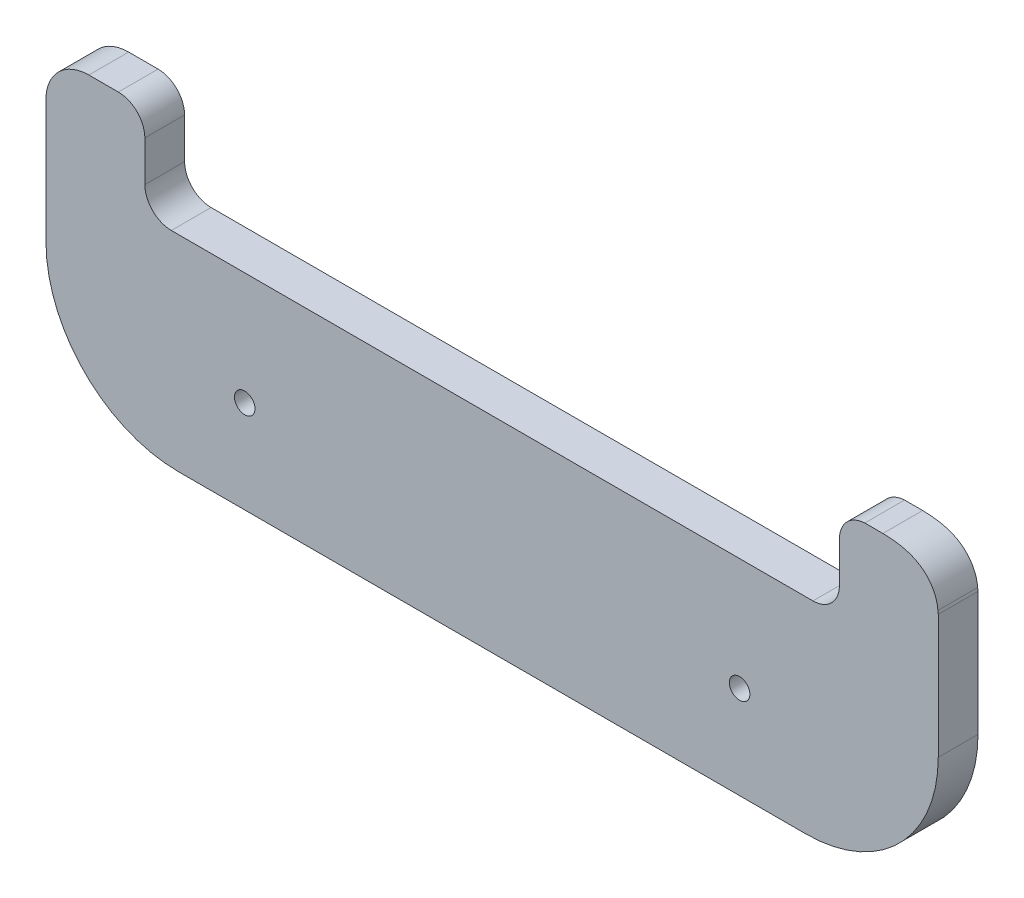
SolidWorks part; units mm, degrees
ref_plane "Płaszczyzna przednia" through (0, 0, 0) normal (0, 0, 1) x (1, 0, 0)
ref_plane "Płaszczyzna górna" through (0, 0, 0) normal (0, 1, 0) x (1, 0, 0)
ref_plane "Płaszczyzna prawa" through (0, 0, 0) normal (1, 0, 0) x (0, 0, -1)
sketch "Szkic1" plane through (0, 0, 0) normal (0, 0, 1) x (1, 0, 0)
  line L0 (559.3031, -401.1962) -> (679.1692, -401.1962)
  line L1 (552.8295, -407.6962) -> (552.8295, -426.2962) construction
  line L3 (667.5241, -446.2962) -> (572.8295, -446.2962) construction
  line L4 (687.5241, -419.2962) -> (687.5241, -426.2962) construction
  line L5 (552.8295, -407.6962) -> (552.8295, -426.2962)
  line L6 (667.5241, -446.2962) -> (572.8295, -446.2962)
  line L7 (687.4745, -407.1052) -> (687.5241, -407.5881)
  line L8 (687.5241, -419.2962) -> (687.5241, -426.2962)
  line L9 (687.5241, -407.5881) -> (687.5241, -419.2962)
  line L11 (552.8295, -407.6962) -> (552.8295, -407.1115)
  arc A0 (559.3031, -401.1962) -> (552.8295, -407.1115) centre (559.3031, -407.6962) ccw
  arc A3 (552.8295, -426.2962) -> (572.8295, -446.2962) centre (572.8295, -426.2962) ccw construction
  arc A4 (667.5241, -446.2962) -> (687.5241, -426.2962) centre (667.5241, -426.2962) ccw construction
  arc A5 (552.8295, -426.2962) -> (572.8295, -446.2962) centre (572.8295, -426.2962) ccw
  arc A6 (667.5241, -446.2962) -> (687.5241, -426.2962) centre (667.5241, -426.2962) ccw
  spline S8 degree 3 poles (687.4745, -407.1052) (687.4609, -406.9451) (687.3995, -406.4401) (687.1064, -405.2473) (686.199, -403.6678) (684.7284, -402.4536) (683.3218, -401.8042) (682.0659, -401.467) (680.9479, -401.2995) (680.1317, -401.2366) (679.5784, -401.2104) (679.3392, -401.2018) (679.2108, -401.1976) (679.1875, -401.1968) (679.1692, -401.1962) knots 0.021401 0.021401 0.021401 0.021401 0.051544 0.115123 0.24228 0.369438 0.496595 0.623753 0.75091 0.878067 0.941646 0.990182 0.996199 1.005225 1.005225 1.005225 1.005225
  point P0 (567.8031, -401.1962)
  point P20 (567.8031, -405.1962)
  point P21 (559.3031, -405.1962)
  point P30 (679.1031, -405.1962)
  point P31 (670.6031, -405.1962)
extrude "Dodanie-wyciągnięcie1" add sketch "Szkic1" along normal blind 6 contours S8 L0 A0 L11 L5 A5 L6 A6 L8 L9 L7
sketch "Szkic4" plane through (0, 0, 6) normal (0, 0, 1) x (1, 0, 0)
  line L1 (598.9031, -405.0685) -> (592.9031, -405.0685)
  line L2 (559.3031, -401.1962) -> (679.1692, -401.1962) construction
  line L5 (589.4031, -408.5685) -> (589.4031, -409.1685)
  line L6 (592.9031, -412.6685) -> (598.9031, -412.6685)
  line L7 (602.4031, -409.1685) -> (602.4031, -408.5685)
  arc A4 (592.9031, -405.0685) -> (589.4031, -408.5685) centre (592.9031, -408.5685) ccw
  arc A5 (589.4031, -409.1685) -> (592.9031, -412.6685) centre (592.9031, -409.1685) ccw
  arc A6 (598.9031, -412.6685) -> (602.4031, -409.1685) centre (598.9031, -409.1685) ccw
  arc A7 (602.4031, -408.5685) -> (598.9031, -405.0685) centre (598.9031, -408.5685) ccw
  dimension "D5" = 13
  dimension "D6" = 3.5
  dimension "D7" = 3.5
  dimension "D3" = 3.5
  dimension "D4" = 3.5
  dimension "D1" = 7.6
  dimension "D2" = 3.8723
  dimension "D9" = 3.5
sketch "Szkic5" plane through (0, 0, 6) normal (0, 0, 1) x (1, 0, 0)
  circle A0 centre (582.8295, -432.2962) radius 1.55 construction
  circle A1 centre (657.5343, -432.2754) radius 1.55 construction
  circle A4 centre (582.8295, -432.2962) radius 1.55
  circle A5 centre (657.5343, -432.2754) radius 1.55
extrude "Wytnij-wyciągnięcie4" cut sketch "Szkic5" against normal blind 6
extrude "Wytnij-wyciągnięcie3" cut sketch "Szkic4" against normal blind 10
ref_plane "Płaszczyzna1" through (559.3031, -401.1962, 6) normal (1, 0, 0) x (0, 0, -1)
sketch "Szkic7" plane through (0, 0, 6) normal (0, 0, 1) x (1, 0, 0)
  line L1 (668.6041, -415.2962) -> (571.7513, -415.2962)
  line L2 (676.5936, -401.1926) -> (563.7513, -401.1962)
  line L3 (567.7513, -411.2962) -> (567.7513, -405.1962)
  line L4 (672.6041, -411.2962) -> (672.6041, -405.1926)
  line L8 (559.3031, -401.1962) -> (679.1692, -401.1962) construction
  arc A0 (563.7513, -401.1962) -> (567.7513, -405.1962) centre (563.7513, -405.1962) cw
  arc A1 (571.7513, -415.2962) -> (567.7513, -411.2962) centre (571.7513, -411.2962) cw
  arc A2 (676.5936, -401.1926) -> (672.6041, -405.1926) centre (676.6041, -405.1926) ccw
  arc A3 (668.6041, -415.2962) -> (672.6041, -411.2962) centre (668.6041, -411.2962) ccw
  point P13 (567.7513, -401.1962)
  dimension "D2" = 4
  dimension "D3" = 4
extrude "Wytnij-wyciągnięcie5" cut sketch "Szkic7" against normal blind 6
